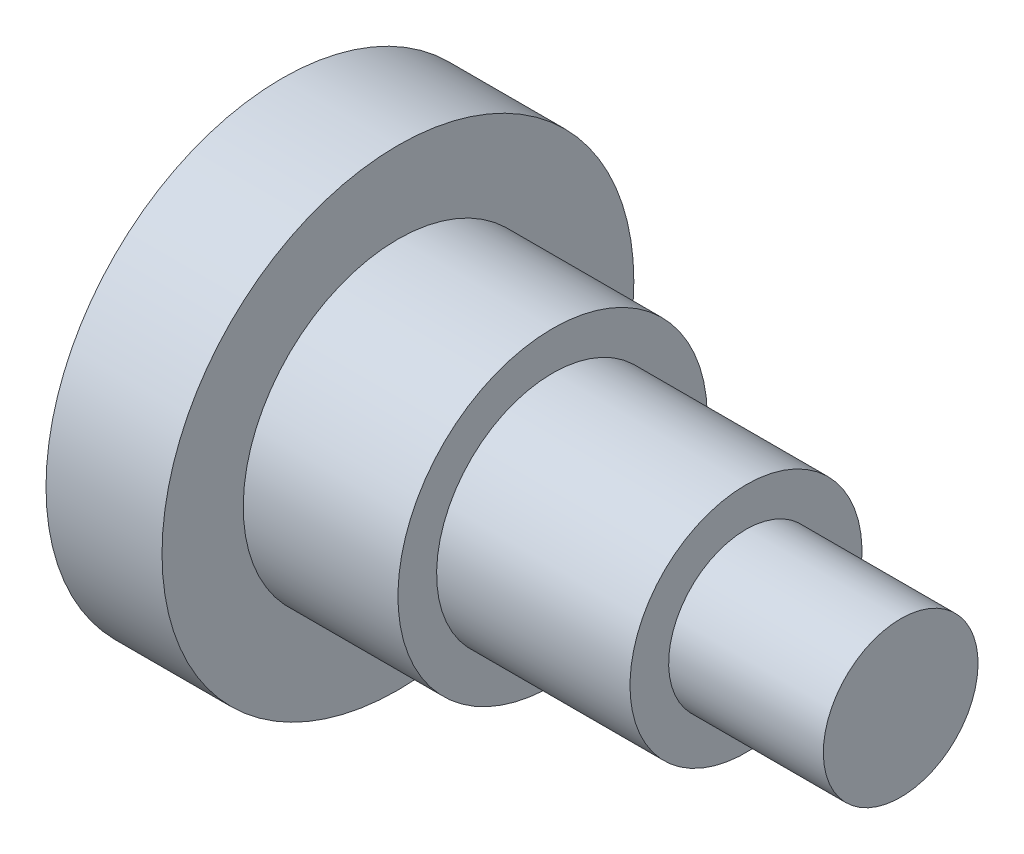
SolidWorks part; units mm, degrees
ref_plane "Piano frontale" through (0, 0, 0) normal (0, 0, 1) x (1, 0, 0)
ref_plane "Piano superiore" through (0, 0, 0) normal (0, 1, 0) x (1, 0, 0)
ref_plane "Piano destro" through (0, 0, 0) normal (1, 0, 0) x (0, 0, -1)
sketch "Schizzo1" plane through (0, 0, 0) normal (0, 0, 1) x (1, 0, 0)
  line L0 (0, 0) -> (0, 30.5)
  line L1 (0, 30.5) -> (15, 30.5)
  line L2 (15, 30.5) -> (15, 20)
  line L3 (15, 20) -> (35, 20)
  line L4 (35, 20) -> (35, 15)
  line L5 (35, 15) -> (60, 15)
  line L6 (60, 15) -> (60, 10)
  line L7 (60, 10) -> (80, 10)
  line L8 (80, 10) -> (80, 0)
  line L9 (80, 0) -> (0, 0) construction
  line L10 (0, 0) -> (80, 0)
  dimension "D1" = 61
  dimension "D2" = 40
  dimension "D3" = 30
  dimension "D4" = 20
  dimension "D5" = 80
  dimension "D6" = 20
  dimension "D7" = 25
  dimension "D8" = 15
revolve "Rivoluzione1" add sketch "Schizzo1" angle 360 about L9
shell "Svuota1" thickness 2
